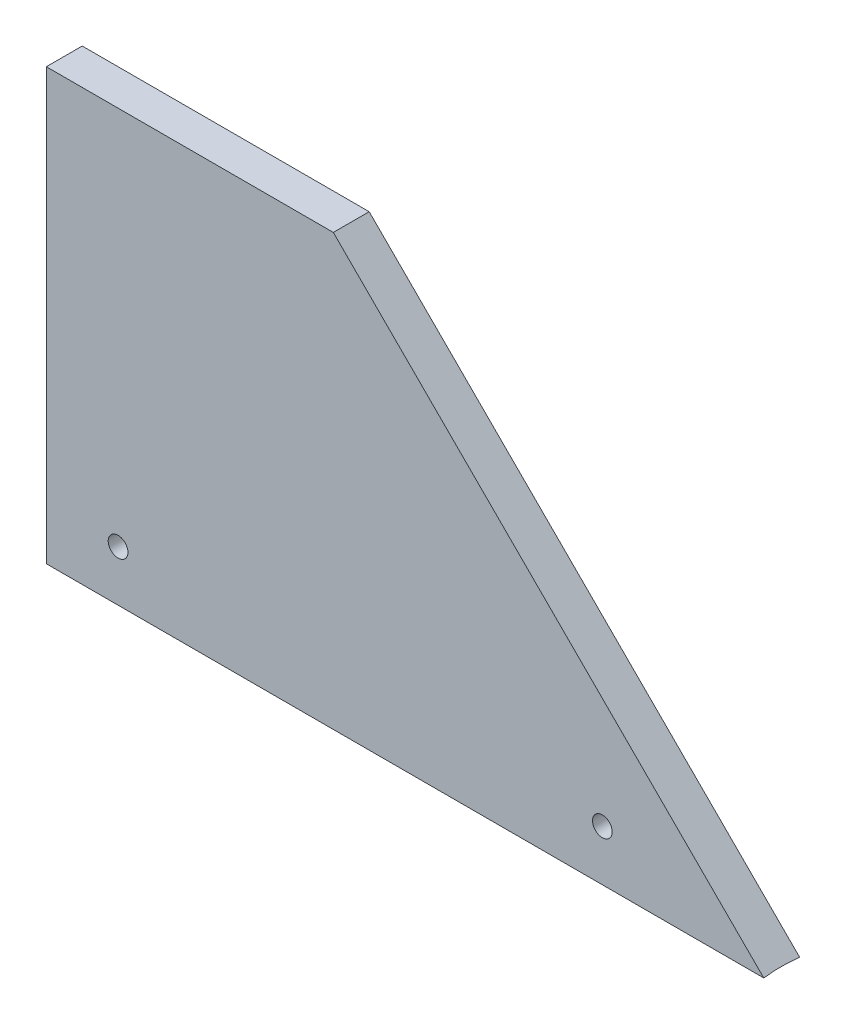
SolidWorks part; units mm, degrees
ref_plane "Plan de face" through (0, 0, 0) normal (0, 0, 1) x (1, 0, 0)
ref_plane "Plan de dessus" through (0, 0, 0) normal (0, 1, 0) x (1, 0, 0)
ref_plane "Plan de droite" through (0, 0, 0) normal (1, 0, 0) x (0, 0, -1)
sketch "Esquisse1" plane through (0, 0, 0) normal (0, 0, 1) x (1, 0, 0)
  line L0 (0, 0) -> (0, 120)
  line L1 (0, 120) -> (80, 120)
  line L2 (80, 120) -> (200, 0)
  line L3 (200, 0) -> (0, 0)
  dimension "D1" = 200
  dimension "D2" = 120
  dimension "D3" = 80
extrude "Boss.-Extru.1" add sketch "Esquisse1" along normal blind 10
sketch "Esquisse2" plane through (0, 0, 0) normal (-1, 0, 0) x (0, 0, 1)
  line L0 (10, 0) -> (0, 0) construction
  arc A0 (10, 0) -> (0, 0) centre (5, -76.0358) ccw
  dimension "D1" = 76.2
extrude "Enlèv. mat.-Extru.1" cut sketch "Esquisse2" against normal through all and the other way through all
ref_plane "Plan1" through (0, 0, 5) normal (0, 0, 1) x (1, 0, 0)
hole_wizard "Dégagement M51" positions "Esquisse3" profile "Esquisse5" hole size "M5" standard "DIN" end condition through all
sketch "Esquisse3" plane through (0, 0, 10) normal (0, 0, 1) x (1, 0, 0)
  point P0 (155, 14.1238)
  point P3 (20, 14.1238)
sketch "Esquisse5" plane through (155, 14.1238, 10) normal (1, 0, 0) x (0, -1, 0)
  line L0 (0, 0) -> (0, 10)
  line L1 (0, 10) -> (2.75, 10)
  line L2 (2.75, 10) -> (2.75, 0)
  line L5 (2.75, 0) -> (0, 0)
  line L11 (0, -6.35) -> (0, 107.95) construction
  dimension "Diamètre du perçage jusqu'au prochain" = 5.5
  dimension "Profondeur du perçage jusqu'au prochain" = 10
